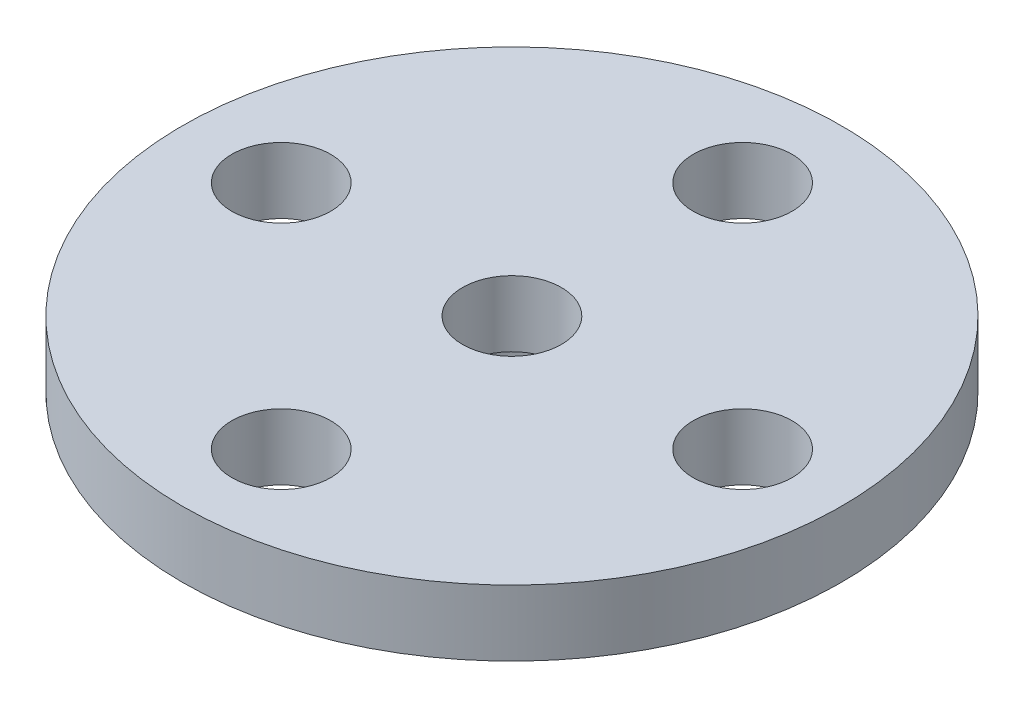
SolidWorks part; units mm, degrees
ref_plane "前视基准面" through (0, 0, 0) normal (0, 0, 1) x (1, 0, 0)
ref_plane "上视基准面" through (0, 0, 0) normal (0, 1, 0) x (1, 0, 0)
ref_plane "右视基准面" through (0, 0, 0) normal (1, 0, 0) x (0, 0, -1)
sketch "草图1" plane through (0, 0, 0) normal (0, 1, 0) x (1, 0, 0)
  line L0 (-12.5399, 0) -> (13.1397, 0) construction
  line L1 (0, 12.2377) -> (0, -11.8787) construction
  circle A0 centre (0, 0) radius 10
  circle A1 centre (-7, 0) radius 1.5
  circle A2 centre (0, 7) radius 1.5
  circle A3 centre (7, 0) radius 1.5
  circle A4 centre (0, -7) radius 1.5
  circle A5 centre (0, 0) radius 1.5
  point P18 (0, 0)
  dimension "D1" = 20
  dimension "D3" = 3
  dimension "D5" = 3
  dimension "D2" = 7
  dimension "D4" = 4
extrude "凸台-拉伸1" add sketch "草图1" along normal blind 2
sketch "草图2" plane through (0, 0, 0) normal (0, 1, 0) x (1, 0, 0)
  circle A0 centre (0, 0) radius 4.5
  circle A1 centre (0, 0) radius 2.75
  dimension "D1" = 9
  dimension "D2" = 5.5
extrude "凸台-拉伸2" add sketch "草图2" against normal blind 2.5
